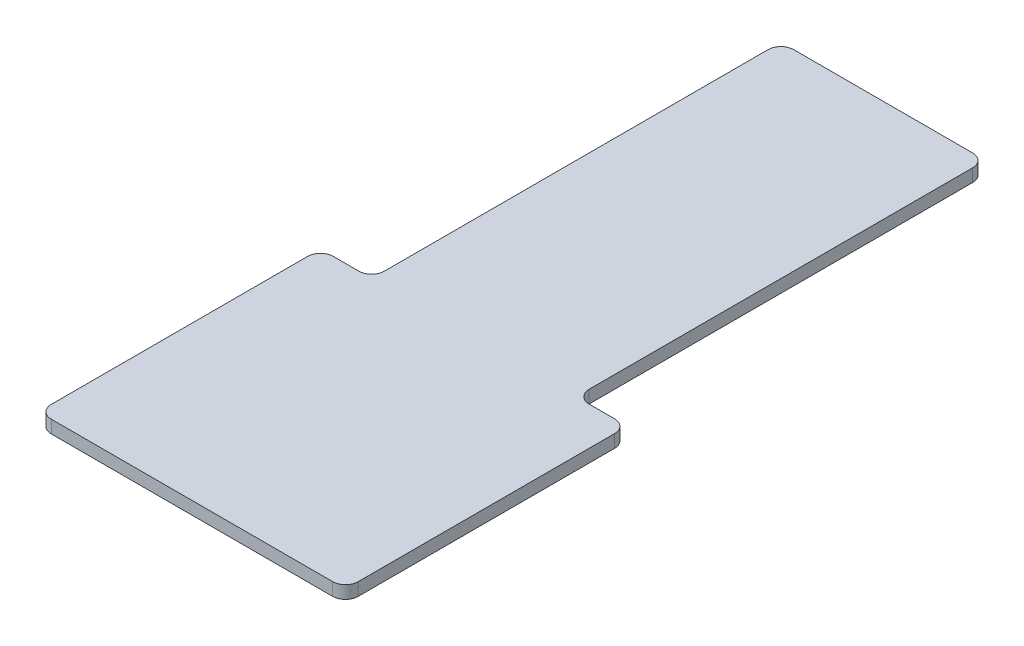
SolidWorks part; units mm, degrees
ref_plane "Front Plane" through (0, 0, 0) normal (0, 0, 1) x (1, 0, 0)
ref_plane "Top Plane" through (0, 0, 0) normal (0, 1, 0) x (1, 0, 0)
ref_plane "Right Plane" through (0, 0, 0) normal (1, 0, 0) x (0, 0, -1)
sketch "Sketch1" plane through (0, 0, 0) normal (0, 1, 0) x (1, 0, 0)
  line L0 (12.7, 70) -> (63.5, 70) construction
  line L1 (0, 0) -> (76.2, 0)
  line L2 (0, 0) -> (0, 70)
  line L3 (0, 70) -> (12.7, 70)
  line L4 (76.2, 0) -> (76.2, 70)
  line L5 (12.7, 70) -> (63.5, 70) construction
  line L6 (12.7, 70) -> (12.7, 171.6)
  line L7 (12.7, 171.6) -> (63.5, 171.6)
  line L8 (63.5, 70) -> (63.5, 171.6)
  line L9 (63.5, 70) -> (76.2, 70)
  point P9 (38.1, 171.6)
  point P10 (38.1, 0)
  dimension "D1" = 76.2
  dimension "D2" = 70
  dimension "D3" = 50.8
  dimension "D4" = 101.6
extrude "Boss-Extrude1" add sketch "Sketch1" along normal blind 3.175
fillet "Fillet1" radius 3.175 8 edges at (0, 1.5875, -70) (12.7, 1.5875, -70) (12.7, 1.5875, -171.6) (63.5, 1.5875, -171.6) (63.5, 1.5875, -70) (76.2, 1.5875, 0) (0, 1.5875, 0) (76.2, 1.5875, -70)
